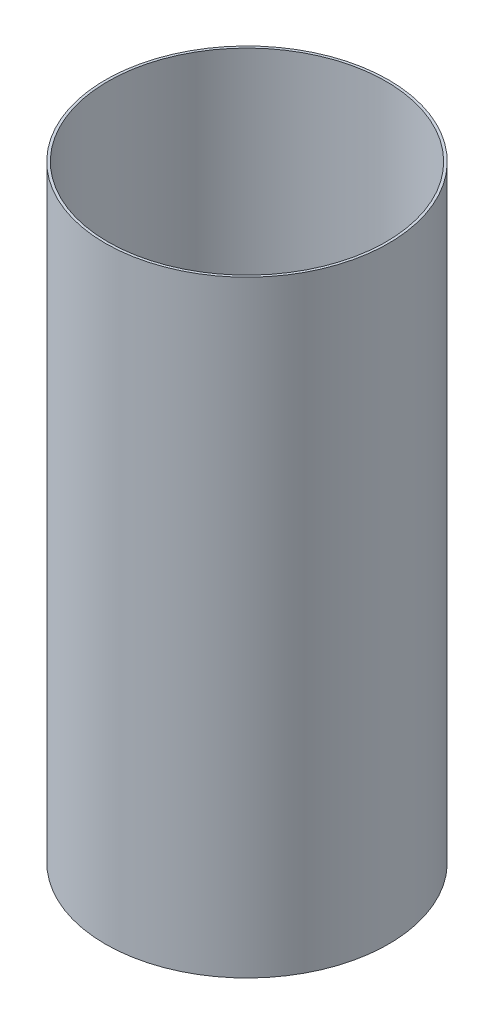
SolidWorks part; units mm, degrees
material "Hexcel AS4C (3000 Filaments)"
ref_plane "Front Plane" through (0, 0, 0) normal (0, 0, 1) x (1, 0, 0)
ref_plane "Top Plane" through (0, 0, 0) normal (0, 1, 0) x (1, 0, 0)
ref_plane "Right Plane" through (0, 0, 0) normal (1, 0, 0) x (0, 0, -1)
sketch "Sketch2" plane through (0, 0, 0) normal (0, 1, 0) x (1, 0, 0)
  circle A0 centre (0, 0) radius 550
  circle A1 centre (0, 0) radius 560
  dimension "D1" = 1100
  dimension "D2" = 10
extrude "Boss-Extrude1" add sketch "Sketch2" along normal blind 2400
